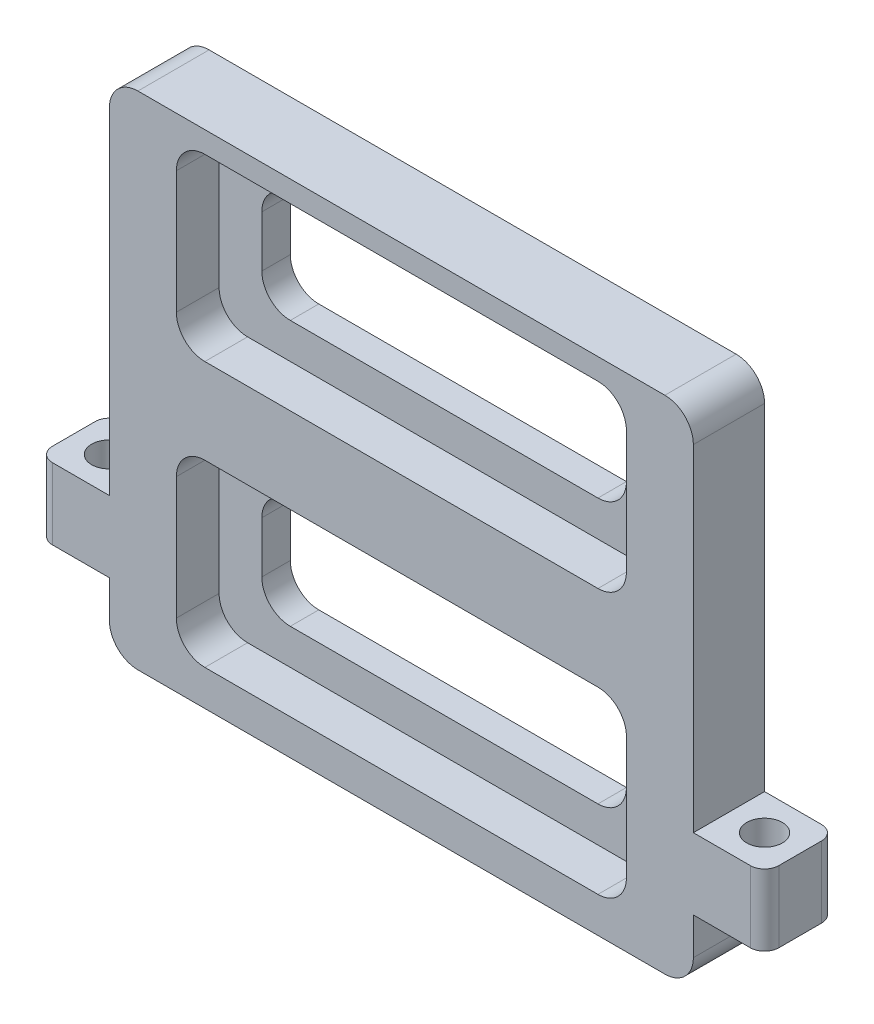
SolidWorks part; units mm, degrees
ref_plane "Front Plane" through (0, 0, 0) normal (0, 0, 1) x (1, 0, 0)
ref_plane "Top Plane" through (0, 0, 0) normal (0, 1, 0) x (1, 0, 0)
ref_plane "Right Plane" through (0, 0, 0) normal (1, 0, 0) x (0, 0, -1)
sketch "Sketch1" plane through (0, 0, 0) normal (0, 0, 1) x (1, 0, 0)
  line L1 (-21, -21.5) -> (21, -21.5)
  line L2 (-21, -21.5) -> (-21, 21.5)
  line L3 (-21, 21.5) -> (21, 21.5)
  line L4 (21, -21.5) -> (21, 21.5)
  line L5 (-21, -21.5) -> (21, 21.5) construction
  line L6 (-21, 21.5) -> (21, -21.5) construction
  point P0 (0, 0)
  dimension "D1" = 42
  dimension "D2" = 43
extrude "Boss-Extrude1" add sketch "Sketch1" along normal blind 5
sketch "Sketch2" plane through (0, 0, 5) normal (0, 0, 1) x (1, 0, 0)
  line L0 (21, 21.5) -> (-21, 21.5) construction
  line L1 (-16.3, 16.3) -> (15.3, 16.3)
  line L2 (-16.3, 16.3) -> (-16.3, 3.7)
  line L3 (-16.3, 3.7) -> (15.3, 3.7)
  line L4 (15.3, 16.3) -> (15.3, 3.7)
  line L5 (-16.3, -2.3) -> (15.3, -2.3)
  line L6 (-16.3, -2.3) -> (-16.3, -14.9)
  line L7 (-16.3, -14.9) -> (15.3, -14.9)
  line L8 (15.3, -2.3) -> (15.3, -14.9)
  line L9 (-21, -21.5) -> (21, -21.5) construction
  line L10 (-21, 21.5) -> (-21, -21.5) construction
  dimension "D1" = 31.6
  dimension "D2" = 12.6
  dimension "D3" = 12.6
  dimension "D4" = 31.6
  dimension "D5" = 5.2
  dimension "D6" = 6.6
  dimension "D7" = 4.7
  dimension "D8" = 4.7
extrude "Cut-Extrude1" cut sketch "Sketch2" against normal blind 3
sketch "Sketch3" plane through (0, 0, 2) normal (0, 0, 1) x (1, 0, 0)
  line L0 (15.3, 16.3) -> (-16.3, 16.3) construction
  line L1 (-13.3, 13.8) -> (12.3, 13.8)
  line L2 (-13.3, 13.8) -> (-13.3, 6.2)
  line L3 (-13.3, 6.2) -> (12.3, 6.2)
  line L4 (12.3, 13.8) -> (12.3, 6.2)
  line L5 (-13.3, -4.8) -> (12.3, -4.8)
  line L6 (-13.3, -4.8) -> (-13.3, -12.4)
  line L7 (-13.3, -12.4) -> (12.3, -12.4)
  line L8 (12.3, -4.8) -> (12.3, -12.4)
  line L9 (-16.3, 16.3) -> (-16.3, 3.7) construction
  line L10 (15.3, 3.7) -> (15.3, 16.3) construction
  line L11 (-16.3, 3.7) -> (15.3, 3.7) construction
  line L12 (15.3, -2.3) -> (-16.3, -2.3) construction
  line L13 (-16.3, -14.9) -> (15.3, -14.9) construction
  line L14 (15.3, -14.9) -> (15.3, -2.3) construction
  line L15 (-16.3, -2.3) -> (-16.3, -14.9) construction
  dimension "D1" = 2.5
  dimension "D2" = 3
  dimension "D3" = 3
  dimension "D4" = 2.5
  dimension "D5" = 2.5
  dimension "D6" = 2.5
  dimension "D7" = 3
  dimension "D8" = 3
extrude "Cut-Extrude2" cut sketch "Sketch3" against normal blind 3
sketch "Sketch4" plane through (0, 0, 0) normal (0, 0, -1) x (-1, 0, 0)
  line L0 (21, 21.5) -> (21, -21.5) construction
  line L1 (-21, 21.5) -> (21, 21.5)
  line L2 (-21, 21.5) -> (-21, 16.3079)
  line L3 (-20, 17.8) -> (21, 17.8)
  line L4 (21, 21.5) -> (21, 16.3079)
  line L5 (-12.3, 13.8) -> (-12.3, 6.2) construction
  line L6 (-21, -21.5) -> (21, -21.5)
  line L7 (-21, -21.5) -> (-21, -16.8347)
  line L8 (-20, -17.4) -> (21, -17.4)
  line L9 (21, -21.5) -> (21, -16.8347)
  line L10 (21, -21.5) -> (16.3138, -21.5)
  line L11 (21, -21.5) -> (21, 21.5)
  line L12 (21, 21.5) -> (16.3138, 21.5)
  line L13 (21, -17.4) -> (21, 17.8)
  line L14 (-21, 21.5) -> (-15.2886, 21.5)
  line L15 (-21, 21.5) -> (-21, -21.5)
  line L16 (-21, -21.5) -> (-15.2886, -21.5)
  line L17 (-20, 17.8) -> (-20, -17.4)
  line L18 (13.3, 13.8) -> (-12.3, 13.8) construction
  line L19 (13.3, 6.2) -> (13.3, 13.8) construction
  line L20 (13.3, -12.4) -> (-12.3, -12.4) construction
  line M9 (-21, 21.5) -> (-21, -21.5)
  line M10 (-21, -21.5) -> (21, -21.5)
  line M11 (21, -21.5) -> (21, 21.5)
  line M12 (21, 21.5) -> (-21, 21.5)
  dimension "D1" = 7.7
  dimension "D2" = 4
  dimension "D3" = 7.7
  dimension "D4" = 5
extrude "Cut-Extrude3" cut sketch "Sketch4" against normal blind 5 contours L1 L6 L17 L3 L13 L8 M12 M9 M10 M11
sketch "Sketch5" plane through (20, 0, 0) normal (1, 0, 0) x (0, 0, -1)
  line L0 (0, 17.8) -> (0, -17.4) construction
  line L1 (0, -12.8) -> (-5, -12.8)
  line L2 (0, -12.8) -> (0, -7.8)
  line L3 (0, -7.8) -> (-5, -7.8)
  line L4 (-5, -12.8) -> (-5, -7.8)
  line L5 (-5, 17.8) -> (-5, -17.4) construction
  line L8 (-5, 17.8) -> (0, 17.8) construction
  dimension "D1" = 25.6
  dimension "D2" = 5
extrude "Boss-Extrude2" add sketch "Sketch5" along normal blind 5
sketch "Sketch6" plane through (-21, 0, 0) normal (-1, 0, 0) x (0, 0, 1)
  line L1 (0, -12.8) -> (5, -12.8)
  line L2 (0, -12.8) -> (0, -7.8)
  line L3 (0, -7.8) -> (5, -7.8)
  line L4 (5, -12.8) -> (5, -7.8)
  line L6 (5, 17.8) -> (0, 17.8) construction
  line L7 (5, 17.8) -> (5, -17.4) construction
  point P10 (0, 0)
  point P11 (0, 0)
  point P12 (0, 0)
  dimension "D1" = 25.6
  dimension "D2" = 5
extrude "Boss-Extrude3" add sketch "Sketch6" along normal blind 5
fillet "Fillet1" radius 2 20 edges at (-13.3, 6.2, 1) (-13.3, 13.8, 1) (12.3, 6.2, 1) (12.3, 13.8, 1) (-13.3, -12.4, 1) (-13.3, -4.8, 1) (12.3, -4.8, 1) (12.3, -12.4, 1) (20, -17.4, 2.5) (20, 17.8, 2.5) (15.3, -14.9, 3.5) (-16.3, -14.9, 3.5) (-16.3, -2.3, 3.5) (15.3, -2.3, 3.5) (15.3, 3.7, 3.5) (-16.3, 3.7, 3.5) (-16.3, 16.3, 3.5) (15.3, 16.3, 3.5) (-21, -17.4, 2.5) (-21, 17.8, 2.5)
sketch "Sketch7" plane through (0, -12.8, 0) normal (0, 1, 0) x (1, 0, 0)
  line L3 (-26, 0) -> (-26, -5) construction
  line L4 (25, -5) -> (25, 0) construction
  point P0 (0, 0)
  point P5 (25, -2.5)
  point P14 (-23.5, -2.5)
  point P15 (22.5, -2.5)
  dimension "D2" = 2.5
  dimension "D1" = 2.5
fillet "Fillet2" radius 1 4 edges at (25, -10.3, 0) (25, -10.3, 5) (-26, -10.3, 0) (-26, -10.3, 5)
hole_wizard "M3x0.5 Tapped Hole1" positions "3DSketch1" profile "Sketch8" tap size "M3x0.5" standard "ANSI Metric"
sketch3d "3DSketch1"
  point P0 (-23.5, -12.8, 2.5)
  point P3 (22.5, -12.8, 2.5)
sketch "Sketch8" plane through (-23.5, -12.8, 2.5) normal (1, 0, 0) x (0, 0, -1)
  line L0 (0, 0) -> (0, 8.2511)
  line L1 (0, 8.2511) -> (1.25, 7.5)
  line L2 (1.25, 7.5) -> (1.25, 0)
  line L5 (1.25, 0) -> (0, 0)
  line L10 (0, 8.2511) -> (-1.25, 7.5) construction
  line L11 (0, -6.35) -> (0, 107.95) construction
  dimension "Tap Drill Dia." = 2.5
  dimension "Tap Drill Depth" = 7.5
  dimension "Drill Angle" = 118
